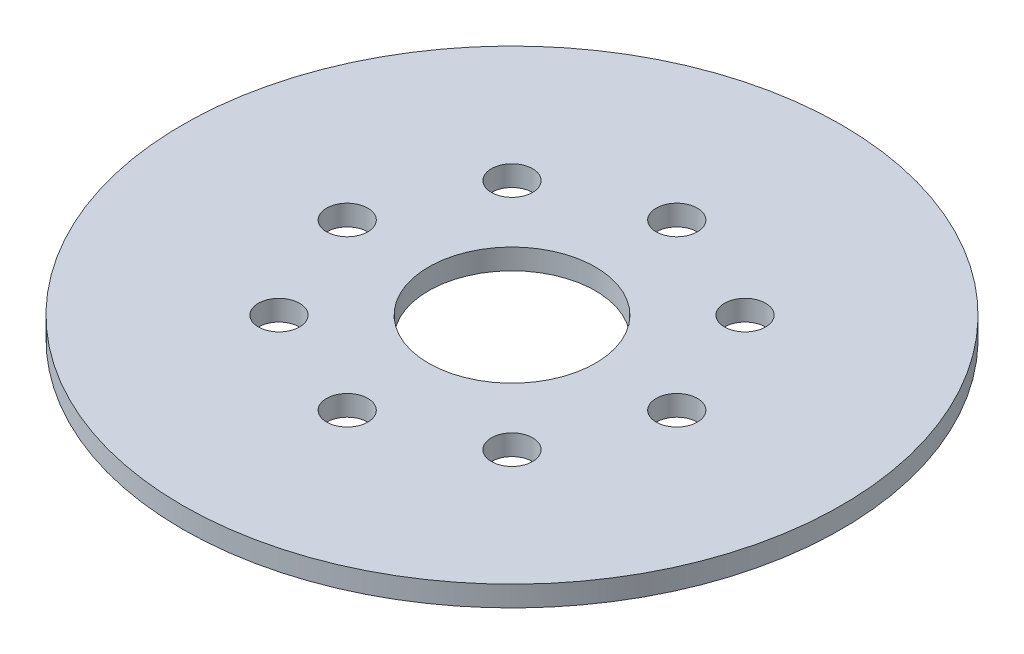
SolidWorks part; units mm, degrees
material "ABS PC"
ref_plane "Front Plane" through (0, 0, 0) normal (0, 0, 1) x (1, 0, 0)
ref_plane "Top Plane" through (0, 0, 0) normal (0, 1, 0) x (1, 0, 0)
ref_plane "Right Plane" through (0, 0, 0) normal (1, 0, 0) x (0, 0, -1)
sketch "Sketch1" plane through (0, 0, 0) normal (0, 1, 0) x (1, 0, 0)
  circle A1 centre (0, 0) radius 4.05
  circle A2 centre (0, 0) radius 16
  circle A3 centre (0, 8) radius 1
  circle A4 centre (5.6569, 5.6569) radius 1
  circle A5 centre (8, 0) radius 1
  circle A6 centre (5.6569, -5.6569) radius 1
  circle A7 centre (0, -8) radius 1
  circle A8 centre (-5.6569, -5.6569) radius 1
  circle A9 centre (-8, 0) radius 1
  circle A10 centre (-5.6569, 5.6569) radius 1
  dimension "D1" = 8
  dimension "D3" = 8.1
  dimension "D4" = 2
extrude "Boss-Extrude1" add sketch "Sketch1" along normal blind 1
